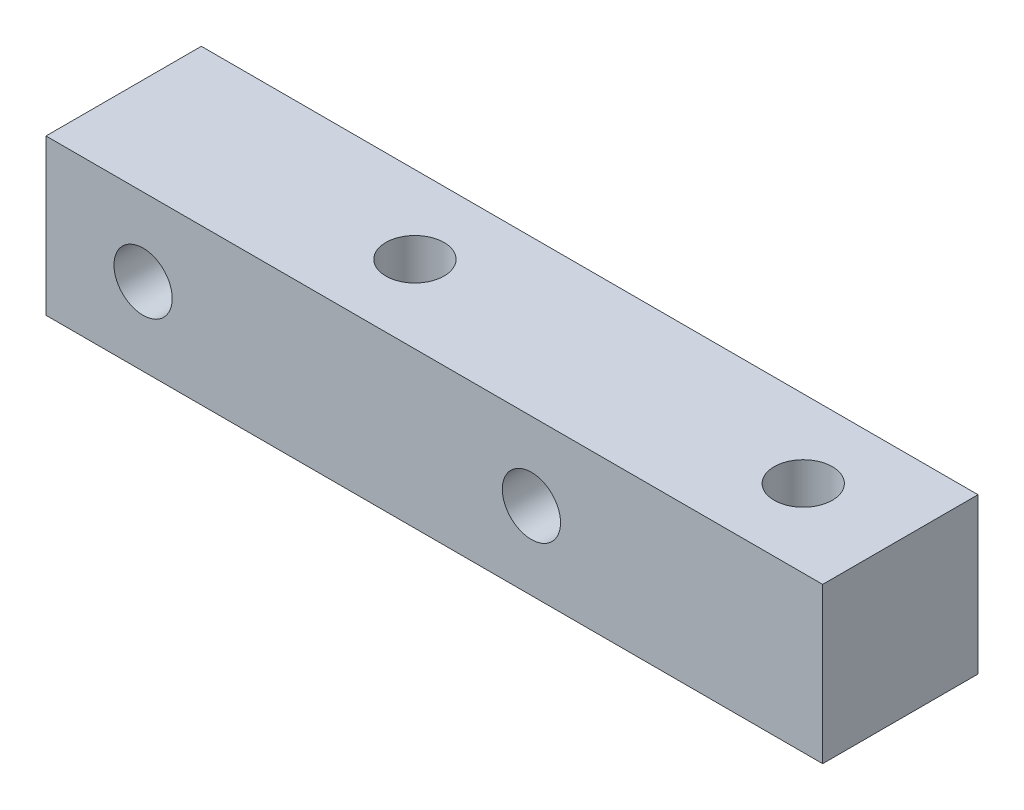
SolidWorks part; units mm, degrees
material "1060 合金"
ref_plane "前视基准面" through (0, 0, 0) normal (0, 0, 1) x (1, 0, 0)
ref_plane "上视基准面" through (0, 0, 0) normal (0, 1, 0) x (1, 0, 0)
ref_plane "右视基准面" through (0, 0, 0) normal (1, 0, 0) x (0, 0, -1)
other "Configuration Table"
sketch "草图1" plane through (0, 0, 0) normal (0, 1, 0) x (1, 0, 0)
  line L1 (-20, -4) -> (20, -4)
  line L2 (-20, -4) -> (-20, 4)
  line L3 (-20, 4) -> (20, 4)
  line L4 (20, -4) -> (20, 4)
  line L5 (-20, -4) -> (20, 4) construction
  line L6 (-20, 4) -> (20, -4) construction
  point P0 (0, 0)
  dimension "D1" = 40
  dimension "D2" = 8
extrude "凸台-拉伸1" add sketch "草图1" along normal blind 8
sketch "草图2" plane through (0, 0, 4) normal (0, 0, 1) x (1, 0, 0)
  line L0 (-20, 4) -> (20, 4) construction
  line L1 (-20, 8) -> (-20, 0) construction
  line L2 (20, 8) -> (20, 0) construction
  circle A0 centre (-15, 4) radius 1.5
  circle A1 centre (5, 4) radius 1.5
  dimension "D1" = 3
  dimension "D2" = 3
  dimension "D3" = 20
  dimension "D4" = 5
extrude "切除-拉伸1" cut sketch "草图2" against normal blind 8
sketch "草图3" plane through (0, 8, 0) normal (0, 1, 0) x (1, 0, 0)
  line L0 (-20, 0) -> (20, 0) construction
  line L1 (-20, 4) -> (-20, -4) construction
  line L2 (20, -4) -> (20, 4) construction
  circle A0 centre (-5, 0) radius 1.5
  circle A1 centre (15, 0) radius 1.5
  dimension "D1" = 3
  dimension "D2" = 3
  dimension "D3" = 20
  dimension "D4" = 5
extrude "切除-拉伸2" cut sketch "草图3" against normal blind 8
